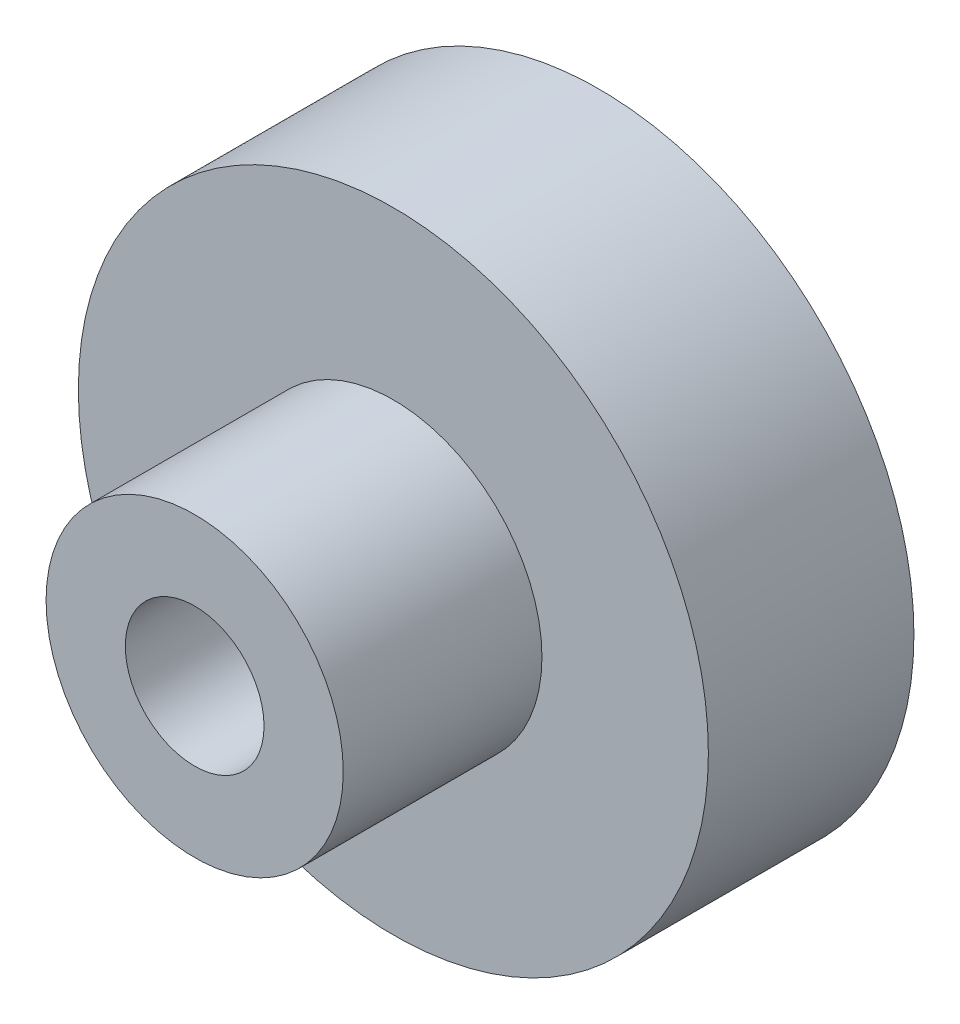
SolidWorks part; units mm, degrees
ref_plane "Alzado" through (0, 0, 0) normal (0, 0, 1) x (1, 0, 0)
ref_plane "Planta" through (0, 0, 0) normal (0, 1, 0) x (1, 0, 0)
ref_plane "Vista lateral" through (0, 0, 0) normal (1, 0, 0) x (0, 0, -1)
sketch "Croquis1" plane through (0, 0, 0) normal (0, 0, 1) x (1, 0, 0)
  circle A0 centre (0, 0) radius 18.39
  dimension "D1" = 36.78
extrude "Saliente-Extruir1" add sketch "Croquis1" along normal mid plane 12
sketch "Croquis3" plane through (0, 0, 6) normal (0, 0, 1) x (1, 0, 0)
  circle A0 centre (0, 0) radius 8.675
  dimension "D1" = 17.35
extrude "Saliente-Extruir2" add sketch "Croquis3" along normal blind 11.6
sketch "Croquis4" plane through (0, 0, 17.6) normal (0, 0, 1) x (1, 0, 0)
  circle A0 centre (0, 0) radius 4.05
  dimension "D1" = 8.1
extrude "Cortar-Extruir1" cut sketch "Croquis4" against normal blind 31.6
